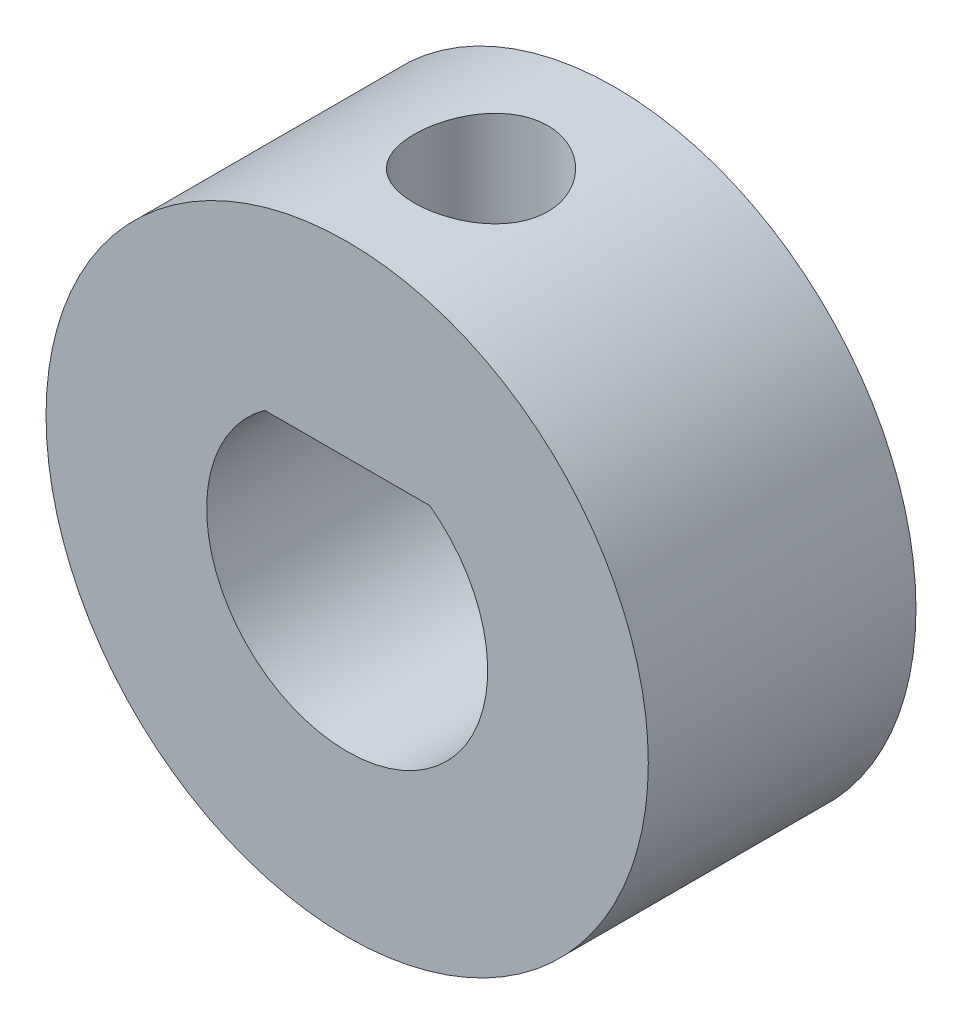
SolidWorks part; units mm, degrees
ref_plane "前视基准面" through (0, 0, 0) normal (0, 0, 1) x (1, 0, 0)
ref_plane "上视基准面" through (0, 0, 0) normal (0, 1, 0) x (1, 0, 0)
ref_plane "右视基准面" through (0, 0, 0) normal (1, 0, 0) x (0, 0, -1)
sketch "草图1" plane through (0, 0, 0) normal (0, 0, 1) x (1, 0, 0)
  line L0 (-1.2329, 1.7) -> (1.2329, 1.7)
  circle A0 centre (0, 0) radius 2.1
  circle A1 centre (0, 0) radius 4.5
  dimension "D1" = 4.2
  dimension "D2" = 9
  dimension "D3" = 1.7
extrude "凸台-拉伸1" add sketch "草图1" along normal blind 4 contours A1 A0 | L0 A0
sketch "草图2" plane through (0, 0, 0) normal (0, 1, 0) x (1, 0, 0)
  line L0 (0, 0) -> (0, -4) construction
  line L1 (-4.5, -4) -> (4.5, -4) construction
  circle A0 centre (0, -2) radius 1
  dimension "D1" = 2
extrude "切除-拉伸1" cut sketch "草图2" along normal through all
